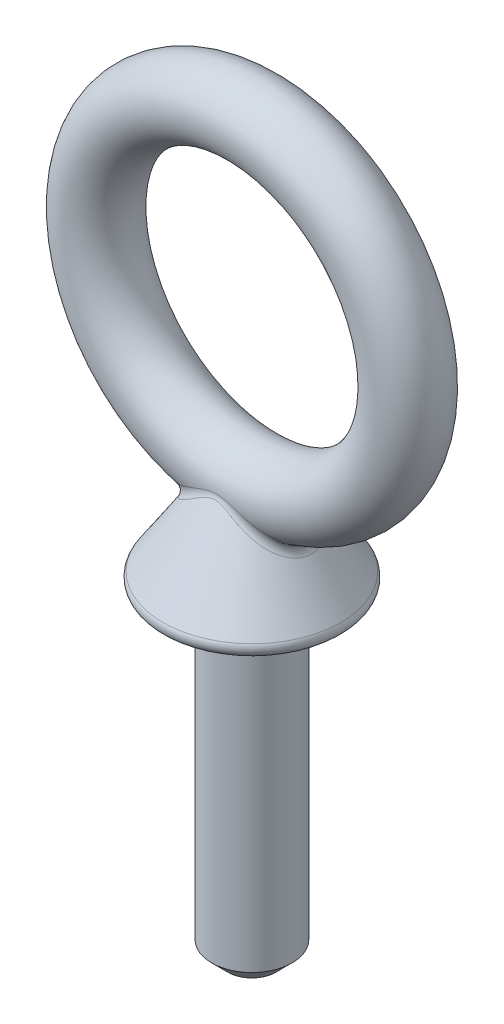
SolidWorks part; units mm, degrees
material "Stainless Steel (ferritic)"
ref_plane "Front Plane" through (0, 0, 0) normal (0, 0, 1) x (1, 0, 0)
ref_plane "Top Plane" through (0, 0, 0) normal (0, 1, 0) x (1, 0, 0)
ref_plane "Right Plane" through (0, 0, 0) normal (1, 0, 0) x (0, 0, -1)
sketch "Sketch1" plane through (0, 0, 0) normal (0, 0, 1) x (1, 0, 0)
  line L0 (0, -15.0812) -> (0, -45.2437) construction
  line L1 (-3.175, -45.2437) -> (3.175, -45.2437) construction
  line L3 (0, -15.0812) -> (0, -9.525) construction
  line L4 (-7.1437, -19.8438) -> (7.1438, -19.8437) construction
  circle A0 centre (0, 0) radius 15.0813 construction
  circle A1 centre (0, 12.3031) radius 2.7781 construction
  circle A2 centre (0, 0) radius 9.525 construction
  point P7 (0, -15.0812)
  point P9 (0, -19.8438)
  point P10 (0, 15.0812)
  point P11 (0, 9.525)
  point P14 (0, -45.2437)
  point P19 (0, -12.3031)
  point P21 (0, -19.8438)
  dimension "A" = 5.5562
  dimension "Eye Dia." = 19.05
  dimension "Overall Lg." = 60.325
  dimension "Shank Lg." = 25.4
  dimension "OD" = 30.1625
  dimension "Thread Lg." = 25.4
  dimension "Thread OD" = 6.35
  dimension "Shoulder Dia." = 14.2875
  dimension "Thickness" = 4.7625
sketch "Sketch2" plane through (0, 0, 0) normal (0, 1, 0) x (1, 0, 0)
  circle A0 centre (0, 0) radius 3.175
extrude "Boss-Extrude1" add sketch "Sketch2" against normal up to vertex (45.2437 mm away) from vertex at -19.8438 starting at point (0, -19.8438, 0)
sketch "Sketch6" plane through (0, 0, 0) normal (1, 0, 0) x (0, 0, -1)
  circle A0 centre (0, 12.3031) radius 2.7781
ref_axis "Axis1" through (0, 0, -7.8581) along (0, 0, 1)
revolve "Revolve1" add sketch "Sketch6" angle 360 about axis through (0, 0, -7.8581) along (0, 0, 1)
sketch "Sketch7" plane through (0, -19.8438, 0) normal (0, 1, 0) x (1, 0, 0)
  circle A1 centre (0, 0) radius 3.175
  circle A2 centre (0, 0) radius 3.175
  dimension "D1" = 0
extrude "Boss-Extrude2" add sketch "Sketch7" along normal up to vertex (9.525 mm away)
sketch "Sketch8" plane through (0, 0, 0) normal (0, 0, 1) x (1, 0, 0)
  line L0 (0, -19.8438) -> (0, -12.3031)
  line L1 (0, -12.3031) -> (-2.7781, -12.3031)
  line L2 (-6.4492, -19.8438) -> (-7.1437, -19.8438) construction
  line L3 (-7.1437, -19.8438) -> (-7.1437, -19.1492) construction
  line L5 (-7.1437, -19.8438) -> (7.1438, -19.8437) construction
  line L6 (-7.0295, -18.7676) -> (-2.7781, -12.3031)
  line L9 (-6.4492, -19.8438) -> (0, -19.8438)
  arc A0 (-7.0295, -18.7676) -> (-6.4492, -19.8438) centre (-6.4492, -19.1492) ccw
  circle A1 centre (0, -12.3031) radius 2.7781 construction
  dimension "D1" = 0.6945
revolve "Revolve2" add sketch "Sketch8" angle 360 about L0
fillet "Fillet1" radius 0.6945 1 edges at (3.7493, -14.1887, 1.4452)
chamfer "Chamfer1" distance 1.27 angle 45 1 edges at (0, -45.2437, 3.175)
